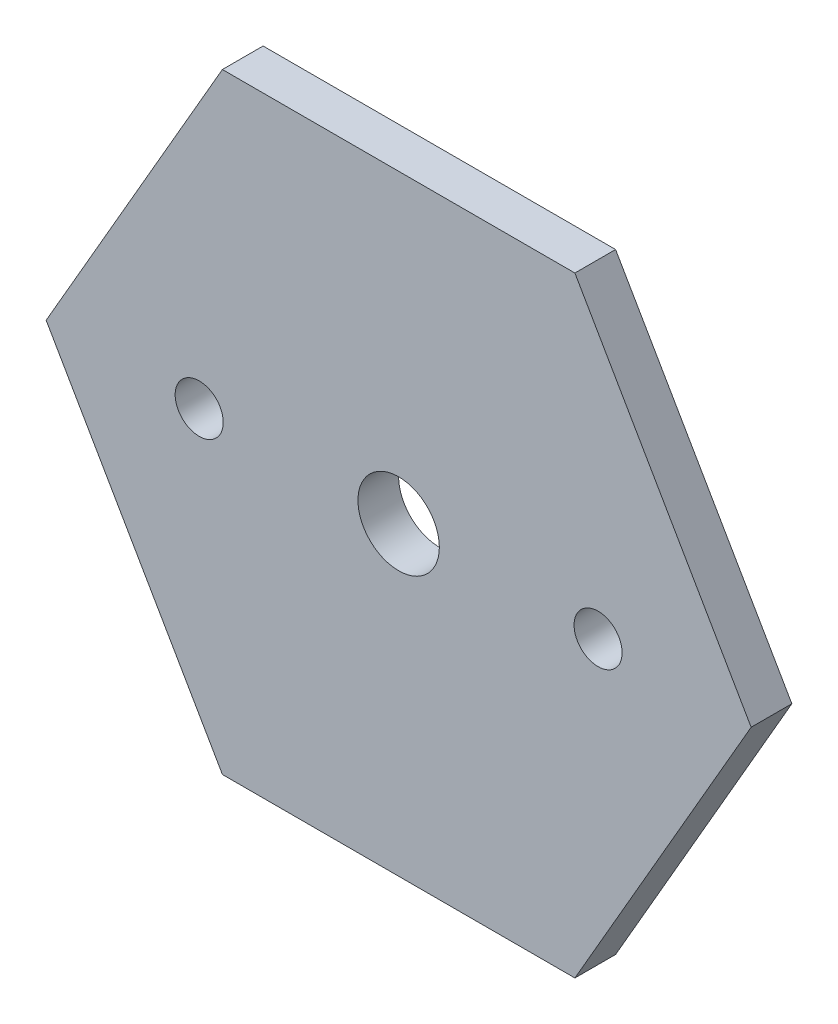
SolidWorks part; units mm, degrees
ref_plane "Front Plane" through (0, 0, 0) normal (0, 0, 1) x (1, 0, 0)
ref_plane "Top Plane" through (0, 0, 0) normal (0, 1, 0) x (1, 0, 0)
ref_plane "Right Plane" through (0, 0, 0) normal (1, 0, 0) x (0, 0, -1)
sketch "Sketch1" plane through (0, 0, 0) normal (0, 0, 1) x (1, 0, 0)
  line L0 (-0.0004, 19.05) -> (0.0004, -19.05) construction
  line L1 (10.9981, 19.0503) -> (-10.999, 19.0497)
  line L2 (-10.999, 19.0497) -> (-21.997, -0.0005)
  line L3 (-21.997, -0.0005) -> (-10.9981, -19.0503)
  line L4 (-10.9981, -19.0503) -> (10.999, -19.0497)
  line L5 (10.999, -19.0497) -> (21.997, 0.0005)
  line L6 (21.997, 0.0005) -> (10.9981, 19.0503)
  line L7 (-21.997, -0.0005) -> (21.997, 0.0005) construction
  circle A0 centre (0, 0) radius 19.05 construction
  circle A1 centre (-12.446, -0.0003) radius 1.5
  circle A2 centre (12.446, 0.0003) radius 1.5
  circle A3 centre (0, 0) radius 2.54
  dimension "D2" = 3
  dimension "D3" = 3
  dimension "D6" = 5.08
  dimension "D1" = 38.1
  dimension "D4" = 12.446
  dimension "D5" = 12.446
extrude "Boss-Extrude1" add sketch "Sketch1" along normal blind 2.54
